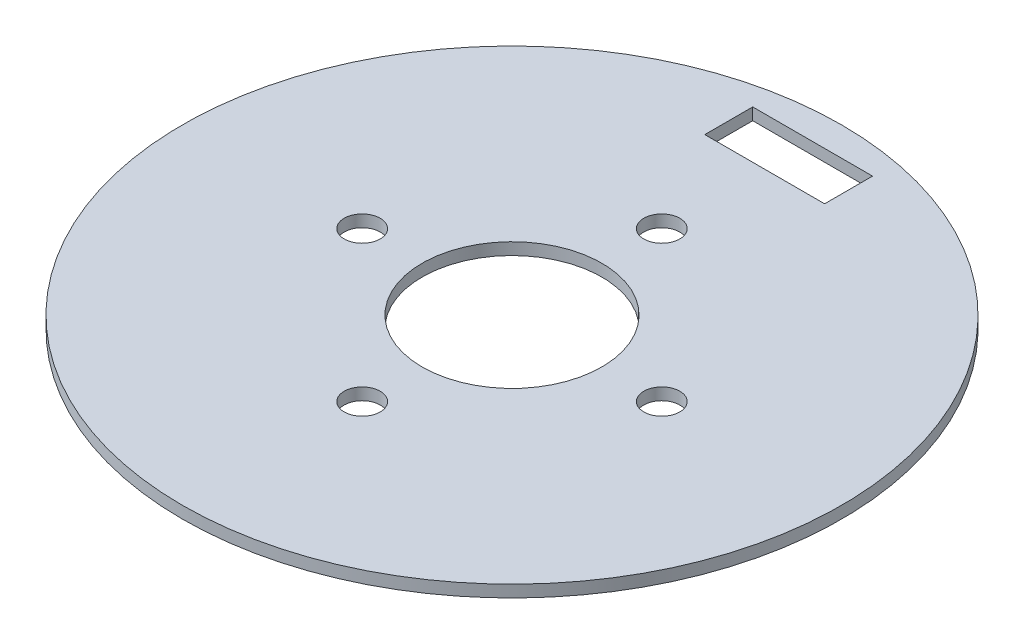
SolidWorks part; units mm, degrees
material "Hexcel AS4C (3000 Filaments)"
ref_plane "Front Plane" through (0, 0, 0) normal (0, 0, 1) x (1, 0, 0)
ref_plane "Top Plane" through (0, 0, 0) normal (0, 1, 0) x (1, 0, 0)
ref_plane "Right Plane" through (0, 0, 0) normal (1, 0, 0) x (0, 0, -1)
sketch "Sketch1" plane through (0, 0, 0) normal (0, 1, 0) x (1, 0, 0)
  line L0 (0, 0) -> (0, 27.5) construction
  line L2 (-5, 25.0864) -> (5, 25.0864)
  line L3 (-5, 25.0864) -> (-5, 21.0864)
  line L4 (-5, 21.0864) -> (5, 21.0864)
  line L5 (5, 25.0864) -> (5, 21.0864)
  line L6 (-5, 25.0864) -> (5, 21.0864) construction
  line L7 (-5, 21.0864) -> (5, 25.0864) construction
  circle A0 centre (0, 0) radius 27.5
  circle A1 centre (0, 0) radius 12.5 construction
  circle A2 centre (0, 12.5) radius 1.5
  circle A3 centre (12.5, 0) radius 1.5
  circle A4 centre (0, -12.5) radius 1.5
  circle A5 centre (-12.5, 0) radius 1.5
  circle A6 centre (0, 0) radius 7.5
  circle A7 centre (0, 0) radius 21 construction
  point P8 (0, 23.0864)
  point P15 (0, 0)
  dimension "D1" = 55
  dimension "D2" = 25
  dimension "D3" = 3
  dimension "D5" = 15
  dimension "D6" = 42
  dimension "D7" = 4
  dimension "D8" = 10
  dimension "D4" = 4
extrude "Boss-Extrude1" add sketch "Sketch1" along normal blind 1
